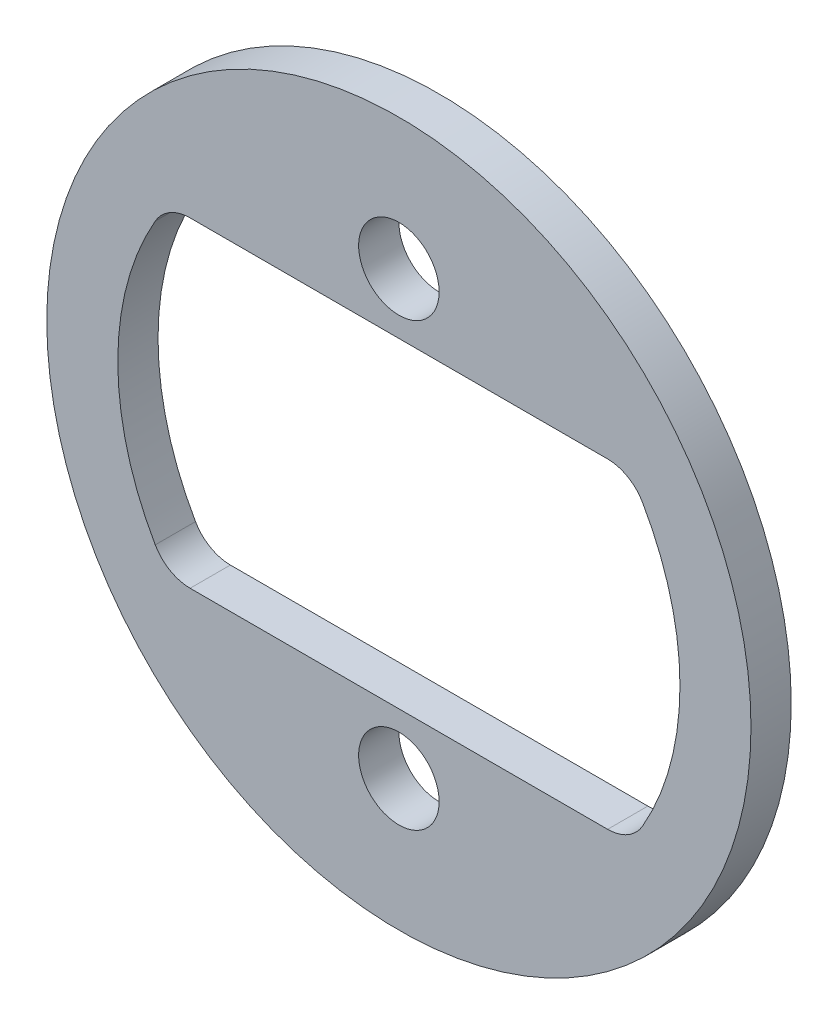
SolidWorks part; units mm, degrees
ref_plane "Front Plane" through (0, 0, 0) normal (0, 0, 1) x (1, 0, 0)
ref_plane "Top Plane" through (0, 0, 0) normal (0, 1, 0) x (1, 0, 0)
ref_plane "Right Plane" through (0, 0, 0) normal (1, 0, 0) x (0, 0, -1)
sketch "Sketch1" plane through (0, 0, 0) normal (0, 0, 1) x (1, 0, 0)
  line L0 (0, 13.97) -> (0, 7.97) construction
  line L1 (11.4734, 7.97) -> (-11.4734, 7.97)
  line L2 (11.4734, 7.97) -> (11.4734, -7.97) construction
  line L3 (11.4734, -7.97) -> (-11.4734, -7.97)
  line L4 (-11.4734, 7.97) -> (-11.4734, -7.97) construction
  line L5 (11.4734, 7.97) -> (-11.4734, -7.97) construction
  line L6 (11.4734, -7.97) -> (-11.4734, 7.97) construction
  line L7 (0, -7.97) -> (0, -13.97) construction
  circle A0 centre (0, 0) radius 17.5
  circle A1 centre (0, 0) radius 13.97
  circle A2 centre (0, -10.97) radius 2
  circle A3 centre (0, 10.97) radius 2
  dimension "D1" = 4
  dimension "D2" = 35
  dimension "D4" = 27.94
  dimension "D3" = 15.94
extrude "Boss-Extrude1" add sketch "Sketch1" along normal blind 2 contours L3 A1 A2 | A0 A1 | L1 A1 A3
fillet "Fillet1" radius 2 4 edges at (-11.4734, -7.97, 1) (11.4734, -7.97, 1) (11.4734, 7.97, 1) (-11.4734, 7.97, 1)
